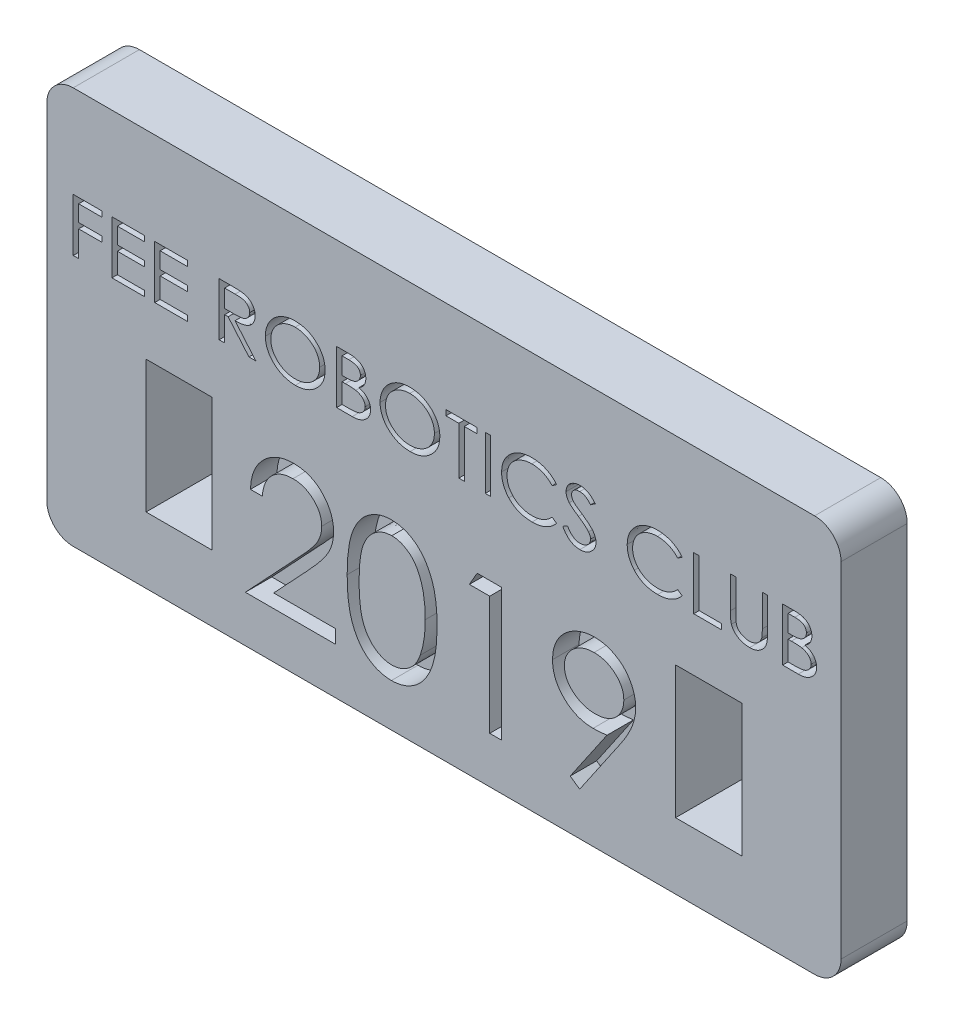
SolidWorks part; units mm, degrees
material "Beech"
ref_plane "Front" through (0, 0, 0) normal (0, 0, 1) x (1, 0, 0)
ref_plane "Top" through (0, 0, 0) normal (0, 1, 0) x (1, 0, 0)
ref_plane "Right" through (0, 0, 0) normal (1, 0, 0) x (0, 0, -1)
sketch "Sketch1" plane through (0, 0, 0) normal (0, 0, 1) x (1, 0, 0)
  line L0 (-14, -7.5) -> (14, -7.5)
  line L1 (-15, -6.5) -> (-15, 6.5)
  line L2 (-14, 7.5) -> (14, 7.5)
  line L3 (15, -6.5) -> (15, 6.5)
  line L4 (-15, -7.5) -> (15, 7.5) construction
  line L5 (-15, 7.5) -> (15, -7.5) construction
  line L10 (0, 1.2617) -> (0, -2.7488) construction
  line L11 (8.75, 0) -> (11.25, 0)
  line L12 (8.75, 0) -> (8.75, -5)
  line L13 (8.75, -5) -> (11.25, -5)
  line L14 (11.25, 0) -> (11.25, -5)
  line L15 (8.75, 0) -> (11.25, -5) construction
  line L16 (8.75, -5) -> (11.25, 0) construction
  line L17 (-8.75, 0) -> (-11.25, 0)
  line L18 (-11.25, 0) -> (-11.25, -5)
  line L19 (-8.75, -5) -> (-11.25, -5)
  line L20 (-8.75, 0) -> (-8.75, -5)
  arc A0 (14, 7.5) -> (15, 6.5) centre (14, 6.5) cw
  arc A1 (14, -7.5) -> (15, -6.5) centre (14, -6.5) ccw
  arc A2 (-14, -7.5) -> (-15, -6.5) centre (-14, -6.5) cw
  arc A3 (-15, 6.5) -> (-14, 7.5) centre (-14, 6.5) cw
  point P0 (0, 0)
  point P5 (10, -2.5)
  dimension "D3" = 1
  dimension "D1" = 30
  dimension "D2" = 15
  dimension "D4" = 5
  dimension "D5" = 2.5
  dimension "D6" = 5
  dimension "D7" = 5
extrude "Boss-Extrude1" add sketch "Sketch1" along normal blind 2.5 contours A3 L1 A2 L0 A1 L3 A0 L2 L11 L14 L13 L12
sketch "Sketch3" plane through (0, 0, 2.5) normal (0, 0, 1) x (1, 0, 0)
  line L0 (-14.4398, 2.0147) -> (14.4398, 2.0147) construction
  line L1 (-8.6628, -5.7497) -> (8.6628, -5.7497) construction
  text T0 "FEE ROBOTICS CLUB" font "Century Gothic" height 2
  text T1 "2019" font "Century Gothic" height 5
  point P5 (0, -5.7497)
  point P7 (0, 2.0147)
extrude "Cut-Extrude2" cut sketch "Sketch3" against normal blind 1
